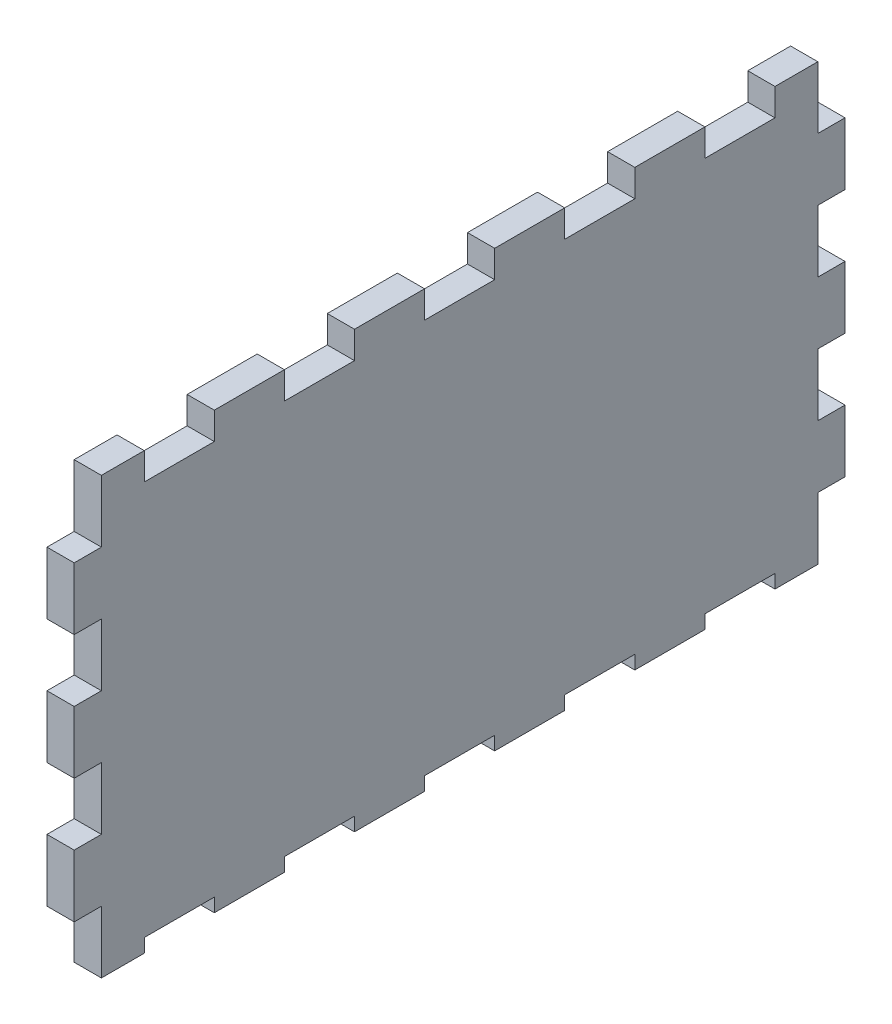
SolidWorks part; units mm, degrees
material "Balsa"
ref_plane "Front" through (0, 0, 0) normal (0, 0, 1) x (1, 0, 0)
ref_plane "Top" through (0, 0, 0) normal (0, 1, 0) x (1, 0, 0)
ref_plane "Right" through (0, 0, 0) normal (1, 0, 0) x (0, 0, -1)
sketch "Esboço1" plane through (0, 0, 0) normal (1, 0, 0) x (0, 0, -1)
  line L1 (85, -48) -> (-85, -48)
  line L2 (85, -48) -> (85, 48)
  line L3 (85, 48) -> (-85, 48)
  line L4 (-85, -48) -> (-85, 48)
  line L5 (85, -48) -> (-85, 48) construction
  line L6 (85, 48) -> (-85, -48) construction
  point P0 (0, 0)
  dimension "D1" = 170
  dimension "D2" = 96
extrude "Ressalto-extrusão1" add sketch "Esboço1" along normal blind 6
sketch "Esboço2" plane through (6, 0, 0) normal (1, 0, 0) x (0, 0, -1)
  line L0 (-7.7255, 42) -> (7.73, 42)
  line L1 (-38.6355, 42) -> (-23.18, 42)
  line L2 (-54.09, 48) -> (-69.5455, 48)
  line L3 (-23.18, 48) -> (-38.6355, 48)
  line L4 (-69.5455, 48) -> (-69.5455, 42)
  line L5 (-54.09, 48) -> (-54.09, 42)
  line L6 (23.1845, 42) -> (38.64, 42)
  line L7 (-38.6355, 48) -> (-38.6355, 42)
  line L8 (7.73, 48) -> (-7.7255, 48)
  line L9 (-23.18, 48) -> (-23.18, 42)
  line L10 (54.0945, 42) -> (69.55, 42)
  line L11 (-7.7255, 48) -> (-7.7255, 42)
  line L12 (38.64, 48) -> (23.1845, 48)
  line L13 (7.73, 48) -> (7.73, 42)
  line L14 (-54.09, -51) -> (-69.5455, -51)
  line L15 (23.1845, 48) -> (23.1845, 42)
  line L16 (-38.6355, -45) -> (-23.18, -45)
  line L17 (38.64, 48) -> (38.64, 42)
  line L18 (-7.7255, -45) -> (7.73, -45)
  line L19 (54.0945, 48) -> (54.0945, 42)
  line L20 (-23.18, -51) -> (-38.6355, -51)
  line L21 (69.55, 48) -> (69.55, 42)
  line L22 (23.1845, -45) -> (38.64, -45)
  line L23 (7.73, -51) -> (-7.7255, -51)
  line L24 (54.0945, -45) -> (69.55, -45)
  line L25 (-54.09, -45) -> (-54.09, -51)
  line L26 (38.64, -51) -> (23.1845, -51)
  line L27 (-38.6355, -45) -> (-38.6355, -51)
  line L29 (-23.18, -45) -> (-23.18, -51)
  line L31 (-7.7255, -45) -> (-7.7255, -51)
  line L33 (7.73, -45) -> (7.73, -51)
  line L35 (23.1845, -45) -> (23.1845, -51)
  line L37 (38.64, -45) -> (38.64, -51)
  line L39 (54.0945, -45) -> (54.0945, -51)
  line L41 (69.55, -45) -> (69.55, -51)
  line L47 (-69.5455, -45) -> (-69.5455, -51)
  line L48 (-69.5455, 42) -> (-54.09, 42)
  line L49 (69.55, 48) -> (54.0945, 48)
  line L50 (-69.5455, -45) -> (-54.09, -45)
  line L51 (69.55, -51) -> (54.0945, -51)
  line L53 (85.0045, 48) -> (85.0045, 42) [skipped]
  line L54 (85.0045, -45) -> (85.0045, -51) [skipped]
  dimension "D1" = 6
  dimension "D3" = 6
  dimension "D4" = 2
extrude "Corte-extrusão1" cut sketch "Esboço2" against normal up to next
sketch "Esboço3" plane through (6, 0, 0) normal (1, 0, 0) x (0, 0, -1)
  line L0 (79, -48) -> (85, -48)
  line L1 (-85, -48) -> (-79, -48)
  line L2 (-85, -48) -> (-85, -34.2857)
  line L3 (-85, -34.2857) -> (-79, -34.2857)
  line L4 (-79, -48) -> (-79, -34.2857)
  line L5 (79, -48) -> (79, -34.2857)
  line L6 (79, -34.2857) -> (85, -34.2857)
  line L7 (85, -48) -> (85, -34.2857)
  line L8 (79, -20.57) -> (85, -20.57)
  line L9 (79, -20.57) -> (79, -6.8557)
  line L10 (79, -6.8557) -> (85, -6.8557)
  line L11 (85, -20.57) -> (85, -6.8557)
  line L12 (79, 6.86) -> (85, 6.86)
  line L13 (79, 6.86) -> (79, 20.5743)
  line L14 (79, 20.5743) -> (85, 20.5743)
  line L15 (85, 6.86) -> (85, 20.5743)
  line L16 (79, 34.29) -> (85, 34.29)
  line L17 (79, 34.29) -> (79, 48.0043)
  line L18 (79, 48.0043) -> (85, 48.0043)
  line L19 (85, 34.29) -> (85, 48.0043)
  line L20 (-85, -20.57) -> (-79, -20.57)
  line L21 (-85, -20.57) -> (-85, -6.8557)
  line L22 (-85, -6.8557) -> (-79, -6.8557)
  line L23 (-79, -20.57) -> (-79, -6.8557)
  line L24 (-85, 6.86) -> (-79, 6.86)
  line L25 (-85, 6.86) -> (-85, 20.5743)
  line L26 (-85, 20.5743) -> (-79, 20.5743)
  line L27 (-79, 6.86) -> (-79, 20.5743)
  line L28 (-85, 34.29) -> (-79, 34.29)
  line L29 (-85, 34.29) -> (-85, 48.0043)
  line L30 (-85, 48.0043) -> (-79, 48.0043)
  line L31 (-79, 34.29) -> (-79, 48.0043)
  dimension "D1" = 6
  dimension "D2" = 13.7143
  dimension "D3" = 2
  dimension "D4" = 4
extrude "Corte-extrusão2" cut sketch "Esboço3" against normal up to next
